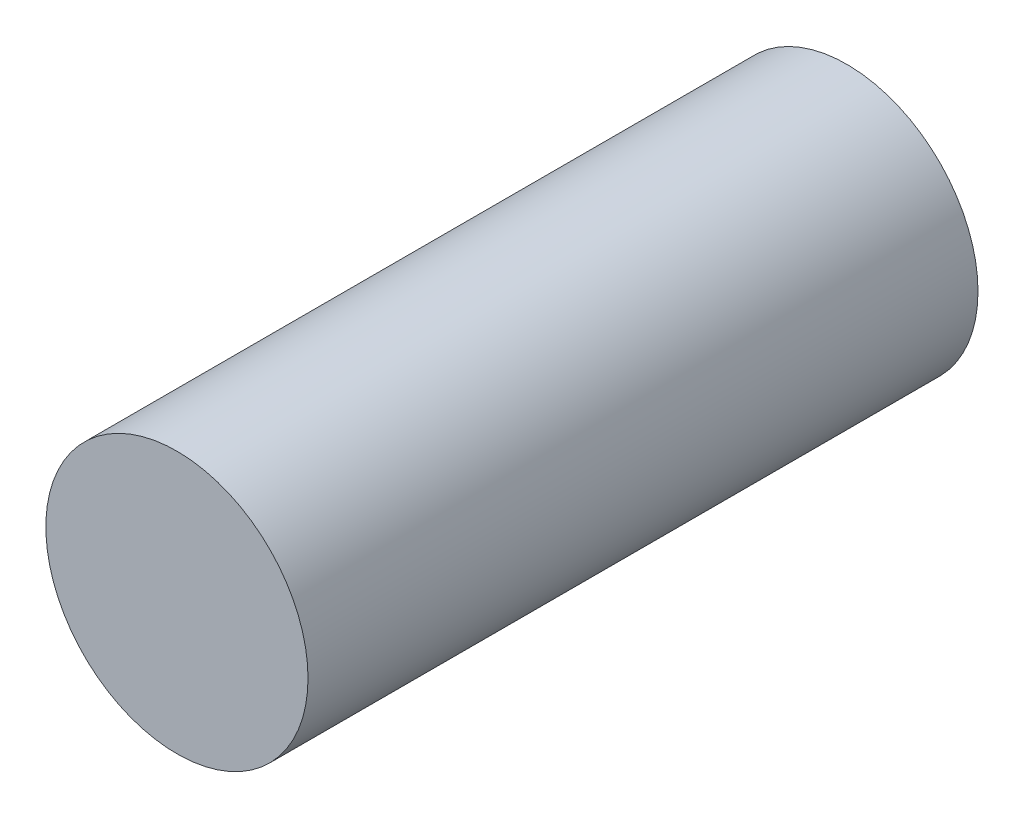
SolidWorks part; units mm, degrees
ref_plane "前视基准面" through (0, 0, 0) normal (0, 0, 1) x (1, 0, 0)
ref_plane "上视基准面" through (0, 0, 0) normal (0, 1, 0) x (1, 0, 0)
ref_plane "右视基准面" through (0, 0, 0) normal (1, 0, 0) x (0, 0, -1)
sketch "草图1" plane through (0, 0, 0) normal (0, 0, 1) x (1, 0, 0)
  circle A0 centre (0, 0) radius 4.5
  dimension "D1" = 9
extrude "凸台-拉伸1" add sketch "草图1" along normal blind 23
